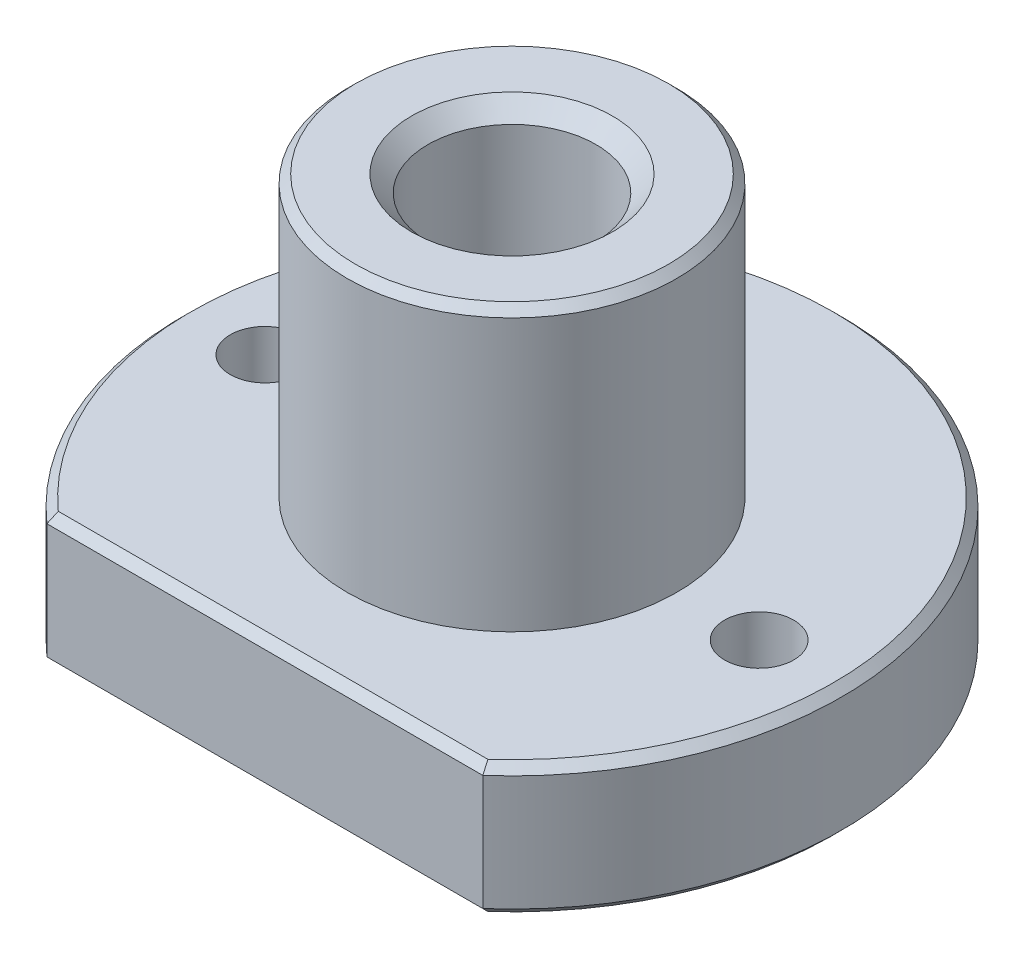
SolidWorks part; units mm, degrees
material "POM Acetal Copolymer"
ref_plane "Front Plane" through (0, 0, 0) normal (0, 0, 1) x (1, 0, 0)
ref_plane "Top Plane" through (0, 0, 0) normal (0, 1, 0) x (1, 0, 0)
ref_plane "Right Plane" through (0, 0, 0) normal (1, 0, 0) x (0, 0, -1)
sketch "Sketch1" plane through (0, 0, 0) normal (0, 1, 0) x (1, 0, 0)
  circle A0 centre (0, 0) radius 20
  dimension "D1" = 40
extrude "Boss-Extrude1" add sketch "Sketch1" along normal blind 8
sketch "Sketch2" plane through (0, 8, 0) normal (0, 1, 0) x (1, 0, 0)
  circle A0 centre (0, 0) radius 10
  dimension "D1" = 20
extrude "Boss-Extrude2" add sketch "Sketch2" along normal blind 17
hole_wizard "M12 Tapped Hole1" positions "Sketch4" profile "Sketch3" tap size "M12" standard "ISO" end condition up to next
sketch "Sketch4" plane through (0, 25, 0) normal (0, 1, 0) x (-1, 0, 0)
  point P1 (0, 0)
sketch "Sketch3" plane through (0, 25, 0) normal (1, 0, 0) x (0, 0, 1)
  line L0 (0, 0) -> (0, 25)
  line L1 (0, 25) -> (5.1, 25)
  line L2 (5.1, 25) -> (5.1, 0)
  line L5 (5.1, 0) -> (0, 0)
  line L11 (0, -6.35) -> (0, 107.95) construction
  dimension "Thru Tap Drill Dia." = 10.2
  dimension "Thru Tap Drill Depth" = 25
cosmetic thread "Hole Thread1" parameters "D2"=12
chamfer "Chamfer1" distance 1 angle 45 2 edges at (0, 0, 5.1) (0, 25, 5.1)
hole_wizard "M5 Tapped Hole1" positions "Sketch6" profile "Sketch5" tap size "M5" standard "ISO" end condition up to next
sketch "Sketch6" plane through (0, 8, 0) normal (0, 1, 0) x (-1, 0, 0)
  line L0 (22.0041, 0) -> (-22.5865, 0) construction
  point P9 (15, 0)
  point P11 (-15, 0)
  dimension "D1" = 15
  dimension "D2" = 30
sketch "Sketch5" plane through (-15, 8, 0) normal (1, 0, 0) x (0, 0, 1)
  line L0 (0, 0) -> (0, 8)
  line L1 (0, 8) -> (2.1, 8)
  line L2 (2.1, 8) -> (2.1, 0)
  line L5 (2.1, 0) -> (0, 0)
  line L11 (0, -6.35) -> (0, 107.95) construction
  dimension "Thru Tap Drill Dia." = 4.2
  dimension "Thru Tap Drill Depth" = 8
cosmetic thread "Hole Thread2" parameters "D2"=5
cosmetic thread "Hole Thread3" parameters "D2"=5
sketch "Sketch7" plane through (0, 0, 0) normal (0, -1, 0) x (1, 0, 0)
  line L1 (-22.5764, 15) -> (26.751, 15)
  line L2 (-22.5764, 15) -> (-22.5764, 28.526)
  line L3 (-22.5764, 28.526) -> (26.751, 28.526)
  line L4 (26.751, 15) -> (26.751, 28.526)
  dimension "D1" = 15
extrude "Cut-Extrude1" cut sketch "Sketch7" against normal up to next
chamfer "Chamfer2" distance 0.5 angle 45 5 edges at (0, 0, 15) (0, 0, -20) (0, 8, 15) (0, 8, -20) (0, 25, 10)
